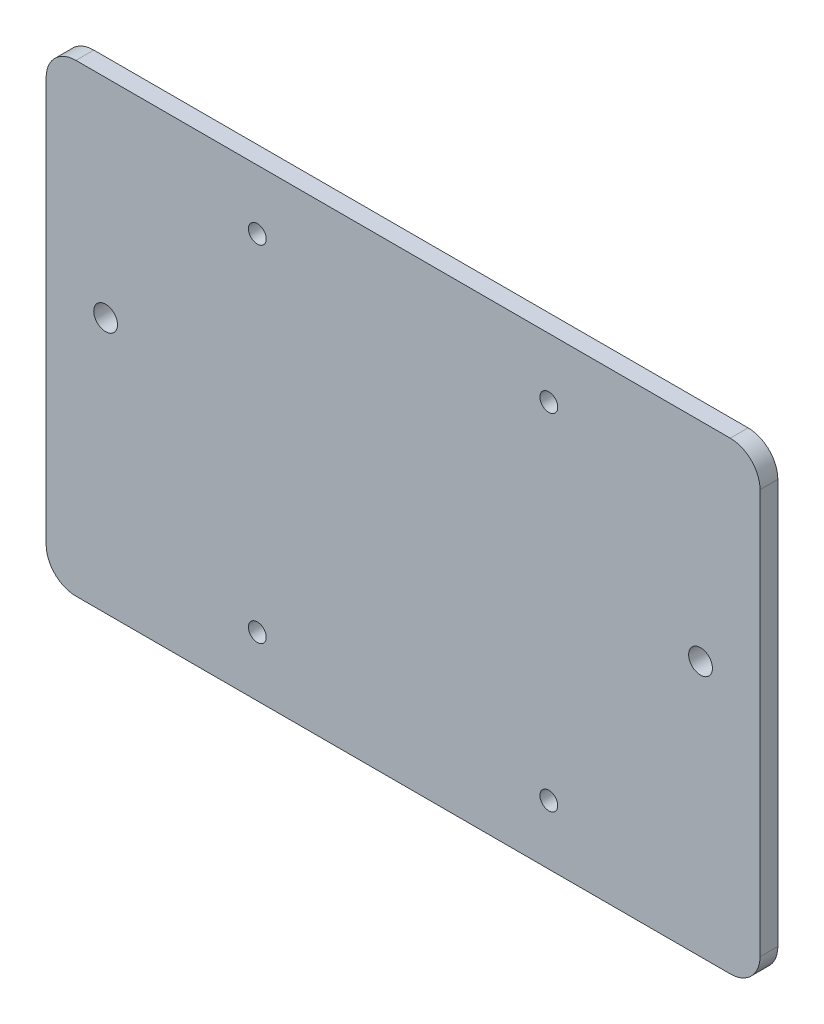
SolidWorks part; units mm, degrees
ref_plane "前基準面" through (0, 0, 0) normal (0, 0, 1) x (1, 0, 0)
ref_plane "上基準面" through (0, 0, 0) normal (0, 1, 0) x (1, 0, 0)
ref_plane "右基準面" through (0, 0, 0) normal (1, 0, 0) x (0, 0, -1)
sketch "草圖1" plane through (0, 0, 0) normal (0, 0, 1) x (1, 0, 0)
  line L0 (0, 39) -> (0, -39) construction
  line L1 (-55, 39) -> (55, 39)
  line L2 (-60, 34) -> (-60, -34)
  line L3 (-55, -39) -> (55, -39)
  line L4 (60, 34) -> (60, -34)
  line L5 (-60, 39) -> (60, -39) construction
  line L6 (-60, -39) -> (60, 39) construction
  line L7 (-24.5, 29) -> (24.5, 29) construction
  line L8 (-24.5, 29) -> (-24.5, -29) construction
  line L9 (-24.5, -29) -> (24.5, -29) construction
  line L10 (24.5, 29) -> (24.5, -29) construction
  line L11 (-24.5, 29) -> (24.5, -29) construction
  line L12 (-24.5, -29) -> (24.5, 29) construction
  circle A0 centre (-24.5, 29) radius 1.5
  circle A1 centre (24.5, 29) radius 1.5
  circle A2 centre (-24.5, -29) radius 1.5
  circle A3 centre (24.5, -29) radius 1.5
  circle A4 centre (50, 4) radius 2
  circle A5 centre (-50, 4) radius 2
  arc A6 (55, 39) -> (60, 34) centre (55, 34) cw
  arc A7 (55, -39) -> (60, -34) centre (55, -34) ccw
  arc A8 (-60, -34) -> (-55, -39) centre (-55, -34) ccw
  arc A9 (-55, 39) -> (-60, 34) centre (-55, 34) ccw
  point P0 (0, 0)
  point P6 (0, 0)
  dimension "D2" = 3
  dimension "D3" = 3
  dimension "D4" = 3
  dimension "D5" = 3
  dimension "D8" = 4
  dimension "D9" = 25
  dimension "D11" = 10
  dimension "D13" = 5
  dimension "D1" = 120
  dimension "D6" = 58
  dimension "D7" = 49
  dimension "D10" = 100
  dimension "D12" = 10
extrude "填料-伸長1" add sketch "草圖1" along normal blind 3
